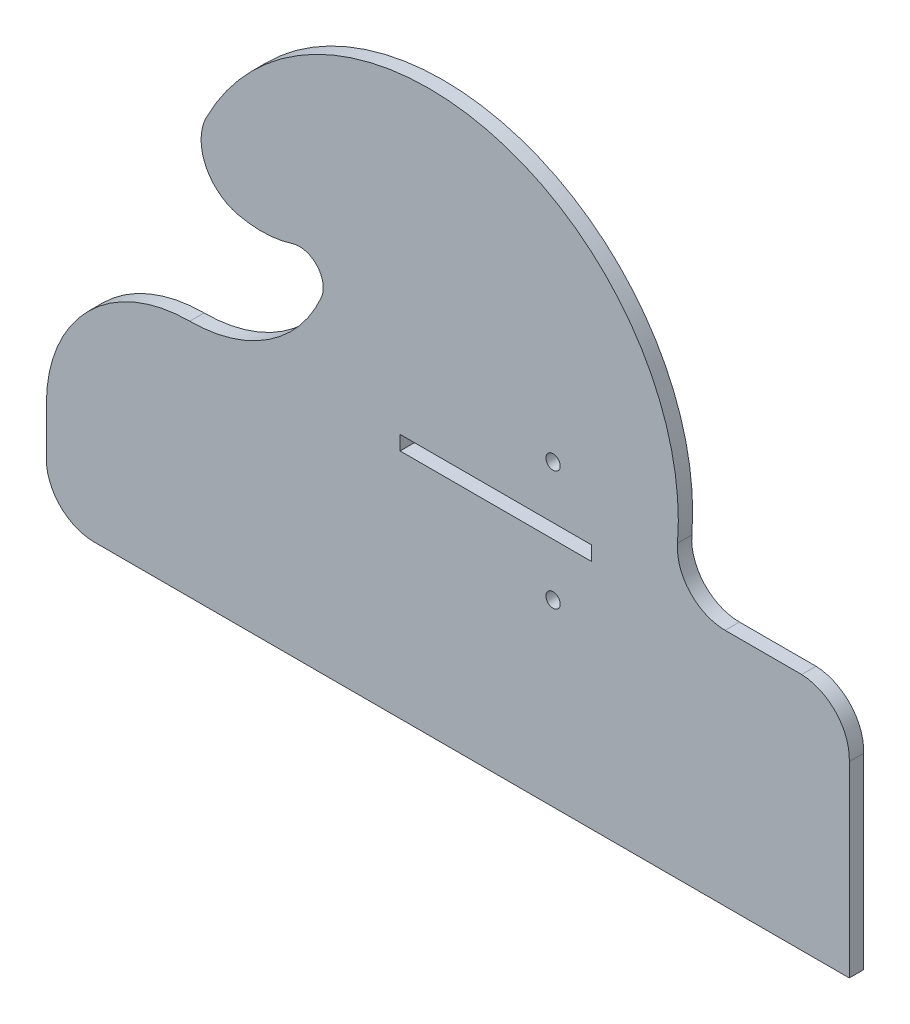
SolidWorks part; units mm, degrees
ref_plane "Plano frontal" through (0, 0, 0) normal (0, 0, 1) x (1, 0, 0)
ref_plane "Plano superior" through (0, 0, 0) normal (0, 1, 0) x (1, 0, 0)
ref_plane "Plano direito" through (0, 0, 0) normal (1, 0, 0) x (0, 0, -1)
sketch "Esboço1" plane through (0, 0, 0) normal (0, 0, 1) x (1, 0, 0)
  line L0 (-33.6967, -9.0229) -> (-3.6967, -9.0229) construction
  line L1 (-3.6967, -9.0229) -> (96.3033, -9.0229) construction
  line L2 (-3.6967, -9.0229) -> (26.3033, -9.0229) construction
  line L3 (-3.6967, -9.0229) -> (-3.6967, 20.9771) construction
  line L4 (108.3035, -9.0229) -> (136.3036, -9.0229) construction
  line L5 (-33.6967, -9.0229) -> (-33.6967, -39.0229) construction
  line L6 (-23.6965, -59.026) -> (126.3036, -59.026)
  line L7 (136.3036, -49.026) -> (136.3036, -19.0229) construction
  line L8 (-33.6967, -39.0229) -> (-33.6965, -49.0262)
  line L9 (108.3035, -9.0229) -> (124.3035, -9.0229)
  line L10 (136.3036, -9.0229) -> (136.3036, -19.0229) construction
  line L12 (134.2712, -9.0229) -> (134.2712, -19.8229) construction
  line L13 (124.3035, -9.0229) -> (134.2712, -9.0229) construction
  line L14 (134.2712, -19.8229) -> (134.2712, -59.0229)
  line L15 (134.2712, -59.0229) -> (126.3036, -59.026)
  arc A0 (-3.6967, -9.0229) -> (23.805, 8.9915) centre (-3.6967, 20.9771) ccw
  arc A1 (6.3253, 15.3569) -> (17.7111, 15.7555) centre (11.3032, 35.9794) ccw
  arc A2 (-0.2454, 29.6038) -> (98.3359, 1.7809) centre (46.3033, 5.9771) cw
  arc A3 (108.3035, -9.0229) -> (98.3359, 1.7809) centre (108.3035, 0.9771) cw
  arc A4 (-0.2454, 29.6038) -> (6.3253, 15.3569) centre (8.6717, 25.0777) ccw
  arc A5 (17.7111, 15.7555) -> (23.805, 8.9915) centre (19.2214, 10.9891) cw
  arc A6 (124.3035, -9.0229) -> (134.2712, -19.8229) centre (123.8862, -19.4078) cw
  arc A7 (136.3036, -49.026) -> (126.3036, -59.026) centre (126.3036, -49.026) cw construction
  arc A8 (-3.6967, -9.0229) -> (-33.6967, -39.0229) centre (-3.6967, -39.0229) ccw
  arc A9 (-23.6965, -59.026) -> (-33.6965, -49.0262) centre (-23.6965, -49.026) cw
  point P24 (136.3036, -59.0229)
  point P27 (-33.6964, -59.026)
  point P30 (-33.6967, -9.026)
  point P32 (-33.6964, -59.026)
  dimension "D5" = 10
  dimension "D6" = 5
  dimension "D9" = 16
  dimension "D11" = 10
  dimension "D1" = 30
  dimension "D2" = 100
  dimension "D3" = 30
  dimension "D4" = 30
  dimension "D7" = 50
  dimension "D8" = 170
  dimension "D10" = 30
  dimension "D13" = 9.9676
  dimension "D14" = 10.8
extrude "Ressalto-extrusão1" add sketch "Esboço1" along normal blind 3
sketch "Esboço2" plane through (0, 0, 3) normal (0, 0, 1) x (1, 0, 0)
  line L0 (108.3035, -9.0229) -> (124.3035, -9.0229) construction
  line L1 (40.3033, -10.5229) -> (80.3035, -10.5229)
  line L2 (40.3033, -10.5229) -> (40.3033, -7.5229)
  line L3 (40.3033, -7.5229) -> (80.3035, -7.5229)
  line L4 (80.3035, -10.5229) -> (80.3035, -7.5229)
  point P6 (116.3035, -9.0229)
  dimension "D1" = 3
  dimension "D2" = 1.5
  dimension "D3" = 44
extrude "Corte-extrusão1" cut sketch "Esboço2" against normal through all
sketch "Esboço3" plane through (0, 0, 3) normal (0, 0, 1) x (1, 0, 0)
  line L0 (124.3035, -9.0229) -> (108.3035, -9.0229) construction
  line L2 (108.3035, -9.0229) -> (124.3035, -9.0229) construction
  circle A0 centre (72.3035, 3.4771) radius 1.5
  circle A1 centre (72.3035, -21.5229) radius 1.5
  dimension "D1" = 3
  dimension "D2" = 3
  dimension "D3" = 12.5
  dimension "D4" = 12.5
  dimension "D5" = 36
  dimension "D6" = 36
extrude "Corte-extrusão2" cut sketch "Esboço3" against normal through all
